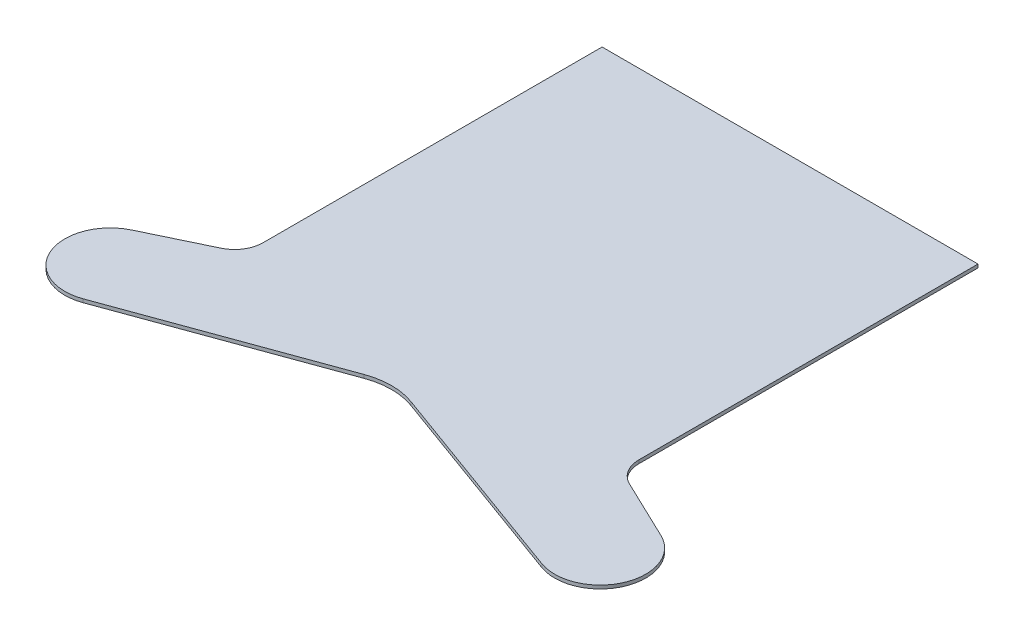
SolidWorks part; units mm, degrees
ref_plane "Front Plane" through (0, 0, 0) normal (0, 0, 1) x (1, 0, 0)
ref_plane "Top Plane" through (0, 0, 0) normal (0, 1, 0) x (1, 0, 0)
ref_plane "Right Plane" through (0, 0, 0) normal (1, 0, 0) x (0, 0, -1)
sketch "Sketch3" plane through (0, 0, 0) normal (0, 1, 0) x (1, 0, 0)
  line L0 (165, 0) -> (998.6493, -303.4235)
  line L1 (0, 0) -> (330, 0)
  line L2 (0, 0) -> (0, 330)
  line L3 (0, 330) -> (330, 330)
  line L4 (330, 0) -> (330, 330)
  line L5 (0, 0) -> (330, 0)
  line L6 (0, 0) -> (0, -60.0551)
  line L7 (0, -60.0551) -> (330, -60.0551)
  line L8 (330, 0) -> (330, -60.0551)
  line L9 (165, 0) -> (-668.6493, -303.4235)
  line L10 (-668.6493, -319.3862) -> (165, -15.9627)
  line L11 (165, -15.9627) -> (998.6493, -319.3862)
  line L12 (-523.6468, -250.6469) -> (0, 0)
  line L13 (-668.6493, -303.4235) -> (0, 16.6298)
  line L14 (15, 0) -> (15, 315)
  line L15 (15, 315) -> (315, 315)
  line L16 (315, 0) -> (315, 315)
  line L17 (0, -25.0551) -> (330, -25.0551)
  line L18 (15, -10.0551) -> (315, -10.0551)
  line L19 (315, -10.0551) -> (315, 0)
  line L20 (15, 0) -> (15, -10.0551)
  line L21 (165, 330) -> (165, 0) construction
  line L22 (998.6493, -303.4235) -> (330, 16.6298)
  line L23 (853.6468, -250.6469) -> (330, 0)
  line L24 (15, 15) -> (315, 15)
  line L25 (-25, 32.3797) -> (15, 32.3797)
  line L26 (-25, 32.3797) -> (-7.7302, -3.7001)
  line L27 (-50, -51.6492) -> (-67.2698, -15.5693)
  line L28 (-50, -51.6492) -> (-36.3192, -89.2369)
  line L29 (165, -79.8133) -> (139.3485, -9.3364)
  line L30 (165, -79.8133) -> (190.6515, -9.3364)
  line L31 (0, 40) -> (15, 40) construction
  line L32 (-23.9741, 5.1545) -> (-17.4979, -8.3755) construction
  line L33 (127.6952, -13.5778) -> (132.8255, -27.6732) construction
  circle A0 centre (-50, -51.6492) radius 40
  circle A1 centre (-50, -51.6492) radius 25
  circle A2 centre (165, -79.8133) radius 75
  circle A3 centre (165, -79.8133) radius 60
  circle A4 centre (380, -51.6492) radius 25
  circle A5 centre (380, -51.6492) radius 40
  circle A6 centre (-25, 32.3797) radius 40
  circle A7 centre (-25, 32.3797) radius 25
  circle A8 centre (355, 32.3797) radius 25
  circle A9 centre (355, 32.3797) radius 40
  dimension "D5" = 150
  dimension "D10" = 80
  dimension "D13" = 80
  dimension "D1" = 330
  dimension "D2" = 330
  dimension "D3" = 15
  dimension "D4" = 15
  dimension "D7" = 15
  dimension "D8" = 35
  dimension "D9" = 70
  dimension "D11" = 50
  dimension "D12" = 15
  dimension "D14" = 290
  dimension "D15" = 48
  dimension "D16" = 180
  dimension "D6" = 15
extrude "Boss-Extrude1" add sketch "Sketch3" along normal blind 3 contours L14 L24 L16 L15 | L16 A9 L4 L3 L2 A6 L14 L15 | L25 A6 L2 | L2 A6 L25 | L26 A6 L2 L13 | L13 A6 L26 | A6 L13 A0 L12 | L12 A0 L27 | L27 A0 L12 | A1 L12 A0 L9 | L9 A0 L28 | L28 A0 L9 | A1 L9 A0 L12 | A0 L9 L6 L12 | A0 L10 L7 L9 | L17 L6 L9 | L20 L1 L6 L17 L9 L18 | A6 L2 L1 L14 | L24 L14 L5 L1 L16 | L5 L20 L18 L9 | A2 L17 L9 L7 L10 | L17 A2 L10 | A2 L18 L9 L17 | L18 A2 L17 L10 L29 | L11 L30 L18 L29 L10 | L29 A2 L18 | L30 A2 L29 L18 | A2 L0 L9 | L18 L19 L1 L0 | A3 L11 L10 | L17 A2 L18 L30 L11 | L11 A2 L17 | A2 L17 L0 L18 | L18 A2 L30 | L19 L18 L0 L17 L8 L5 | A2 L18 L0 | A2 L9 L18 | A6 L12 L2 | A2 L11 L7 L0 L17 | L17 L0 L8 | L11 A5 L0 L7 | L0 A5 L23 L8 | A5 L0 | A5 L23 A4 L0 | A4 | A5 L0 A4 L23 | A5 L23 | L22 A9 L23 A5 | A9 L22 L4 | L4 A9 L16 L5 | L23 A9 L4 | A9 L4 | L22 A8 L4 | A7 L13 L2
sketch "Sketch4" plane through (0, 3, 0) normal (0, 1, 0) x (1, 0, 0)
  line L0 (0, 58.3508) -> (94.427, -41.6492)
  line L1 (-90, 58.3508) -> (420, 58.3508)
  line L2 (-90, 58.3508) -> (-90, -91.6492)
  line L3 (-90, -91.6492) -> (420, -91.6492)
  line L4 (420, 58.3508) -> (420, -91.6492)
  line L5 (0, 32.3797) -> (0, 330) construction
  line L6 (-36.3192, -89.2369) -> (144.4788, -23.4318) construction
  line L7 (94.427, -41.6492) -> (235.573, -41.6492)
  line L8 (185.5212, -23.4318) -> (366.3192, -89.2369) construction
  line L9 (235.573, -41.6492) -> (330, 58.3508)
  line L10 (330, 32.3797) -> (330, 330) construction
  arc A0 (-67.2698, -15.5693) -> (-36.3192, -89.2369) centre (-50, -51.6492) ccw construction
  arc A1 (366.3192, -89.2369) -> (397.2698, -15.5693) centre (380, -51.6492) ccw construction
  point P16 (0, 0)
  arc M6 (-67.2698, -15.5693) -> (-36.3192, -89.2369) centre (-50, -51.6492) ccw
  line M7 (-36.3192, -89.2369) -> (144.4788, -23.4318)
  line M9 (185.5212, -23.4318) -> (366.3192, -89.2369)
  arc M10 (366.3192, -89.2369) -> (397.2698, -15.5693) centre (380, -51.6492) ccw
  line M11 (397.2698, -15.5693) -> (344.2064, 9.8298)
  arc M12 (344.2064, 9.8298) -> (330, 32.3797) centre (355, 32.3797) cw
  line M13 (330, 32.3797) -> (330, 330)
  line M15 (0, 330) -> (0, 32.3797)
  arc M16 (0, 32.3797) -> (-14.2064, 9.8298) centre (-25, 32.3797) cw
  line M17 (-14.2064, 9.8298) -> (-67.2698, -15.5693)
  dimension "D1" = 150
  dimension "D2" = 50
extrude "Cut-Extrude1" [suppressed] cut sketch "Sketch4" against normal through all contours L0 M15 M16 M17 M6 M7 | L1 L2 M6 M17 M16 M15 | L2 L3 M6 | L7 L3 M7 M6 M10 M9 | L9 M9 M10 M11 M12 M13 | L4 L1 M13 M12 M11 M10 | L4 L3 M10
